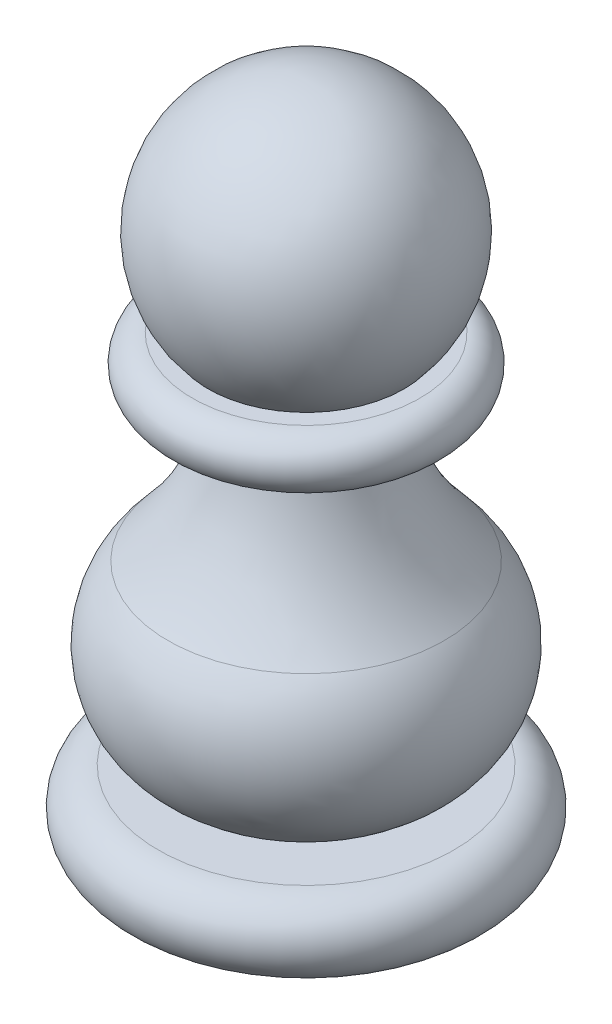
SolidWorks part; units mm, degrees
material "PBT General Purpose"
ref_plane "Front Plane" through (0, 0, 0) normal (0, 0, 1) x (1, 0, 0)
ref_plane "Top Plane" through (0, 0, 0) normal (0, 1, 0) x (1, 0, 0)
ref_plane "Right Plane" through (0, 0, 0) normal (1, 0, 0) x (0, 0, -1)
sketch "Sketch3" plane through (0, 0, 0) normal (0, 0, 1) x (1, 0, 0)
  line L0 (0, 0) -> (0, 38) construction
  line L1 (-5.5902, 25.5) -> (-6.5, 25.5)
  line L4 (-6.5, 22.5) -> (-4, 22.5)
  line L5 (0, 0) -> (-8.442, 0)
  line L6 (-8.442, 4.116) -> (-3.4993, 4.116)
  line L7 (0, 0) -> (0, 38)
  arc A2 (0, 38) -> (-5.5902, 25.5) centre (0, 30.5) ccw
  arc A3 (-6.5, 25.5) -> (-6.5, 22.5) centre (-6.5, 24) ccw
  arc A4 (-8.442, 0) -> (-8.442, 4.116) centre (-8.442, 2.058) cw
  arc A5 (-3.4993, 4.116) -> (-7.8929, 14.2021) centre (-3.4993, 10.116) cw
  arc A6 (-4, 22.5) -> (-7.8929, 14.2021) centre (-18.877, 24.4172) cw
  point P17 (-10.5, 2.058)
  point P18 (-8, 24)
  point P19 (-9, 7.7198)
  dimension "D1" = 6
  dimension "D2" = 7.5
  dimension "D4" = 12.5
  dimension "D6" = 15
  dimension "D11" = 4
  dimension "D3" = 3
  dimension "D5" = 38
  dimension "D7" = 4.116
  dimension "D8" = 10.5
  dimension "D9" = 8
  dimension "D10" = 9
revolve "Revolve1" add sketch "Sketch3" angle 360 about L0
